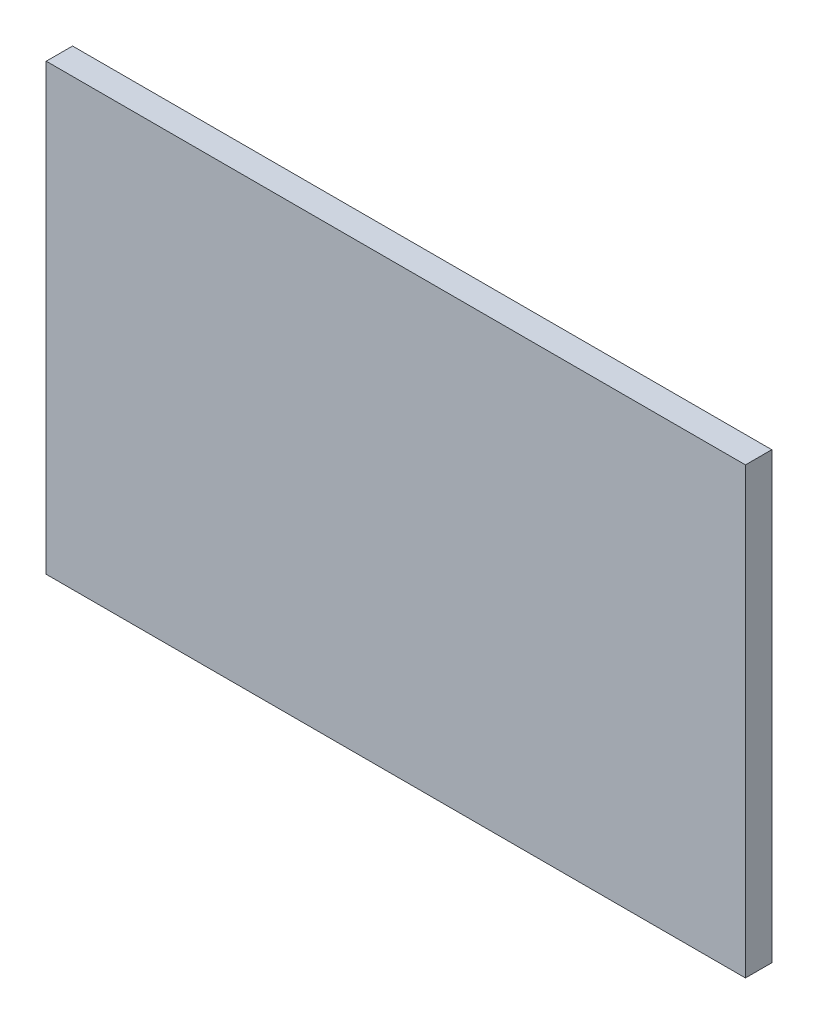
SolidWorks part; units mm, degrees
ref_plane "Front Plane" through (0, 0, 0) normal (0, 0, 1) x (1, 0, 0)
ref_plane "Top Plane" through (0, 0, 0) normal (0, 1, 0) x (1, 0, 0)
ref_plane "Right Plane" through (0, 0, 0) normal (1, 0, 0) x (0, 0, -1)
sketch "Sketch1" plane through (0, 0, 0) normal (0, 0, 1) x (1, 0, 0)
  line L1 (265.684, -168.8522) -> (-265.684, -168.8522)
  line L2 (265.684, -168.8522) -> (265.684, 168.8522)
  line L3 (265.684, 168.8522) -> (-265.684, 168.8522)
  line L4 (-265.684, -168.8522) -> (-265.684, 168.8522)
  line L5 (265.684, -168.8522) -> (-265.684, 168.8522) construction
  line L6 (265.684, 168.8522) -> (-265.684, -168.8522) construction
  point P0 (0, 0)
  dimension "D1" = 629.6
  dimension "D2" = 531.368
extrude "Boss-Extrude1" add sketch "Sketch1" along normal blind 20
